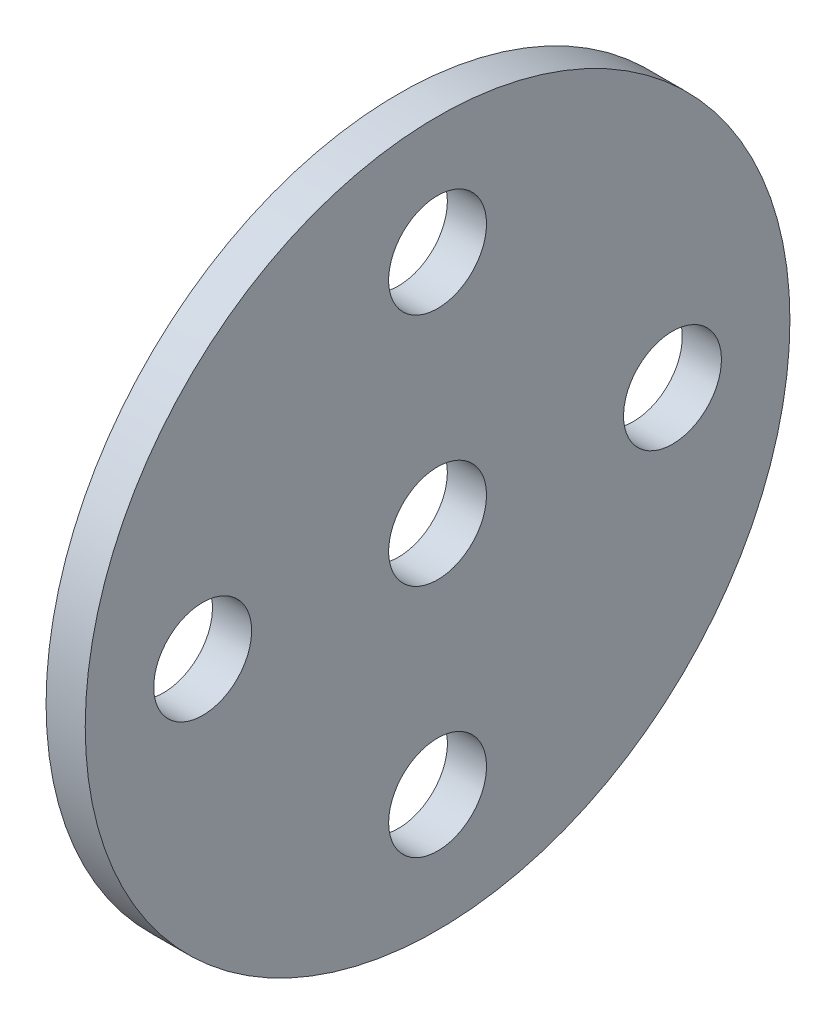
SolidWorks part; units mm, degrees
ref_plane "Front Plane" through (0, 0, 0) normal (0, 0, 1) x (1, 0, 0)
ref_plane "Top Plane" through (0, 0, 0) normal (0, 1, 0) x (1, 0, 0)
ref_plane "Right Plane" through (0, 0, 0) normal (1, 0, 0) x (0, 0, -1)
sketch "Sketch1" plane through (0, 0, 0) normal (1, 0, 0) x (0, 0, -1)
  circle A0 centre (0, 0) radius 28.575
  circle A1 centre (0, 0) radius 3.9688
  circle A2 centre (0, 0) radius 11.1125 construction
  dimension "D1" = 7.9375
  dimension "OD" = 57.15
  dimension "D2" = 22.225
extrude "Boss-Extrude1" add sketch "Sketch1" along normal blind 3.175
sketch "Sketch2" plane through (0, 0, 0) normal (1, 0, 0) x (0, 0, -1)
  line L0 (-28.575, 0) -> (28.575, 0) construction
  circle A0 centre (0, 19.05) radius 3.9688
  circle A1 centre (0, 0) radius 28.575 construction
  point P12 (0, 0)
  dimension "D2" = 7.9375
  dimension "D1" = 19.05
extrude "Cut-Extrude1" cut sketch "Sketch2" along normal through all
pattern_circular "CirPattern1" count 4 over 360 about axis through (0, 0, 0) along (1, 0, 0) of "Cut-Extrude1"
